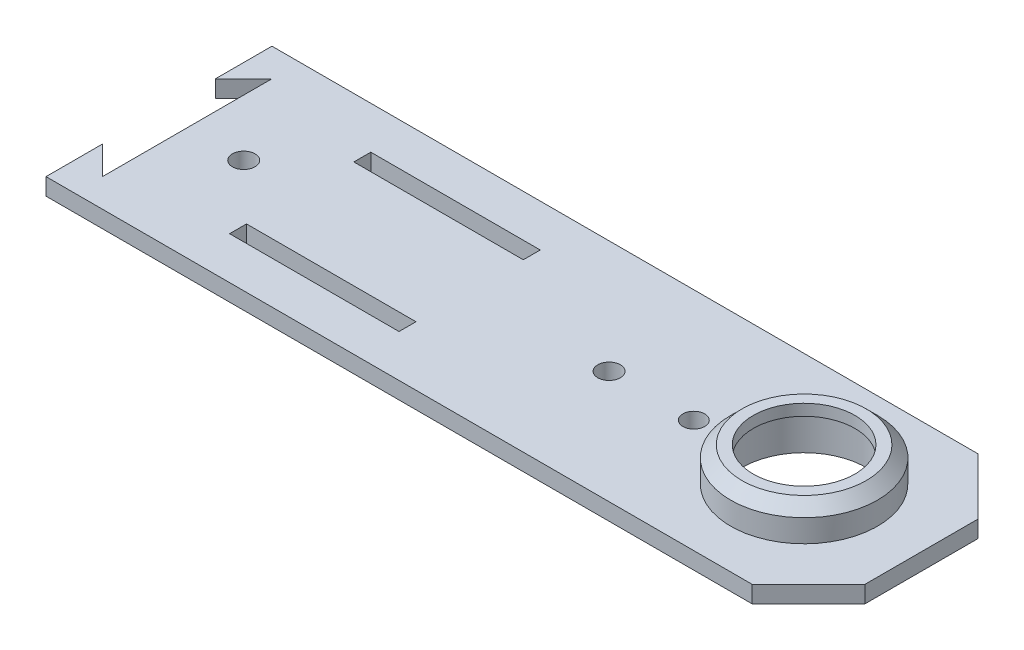
SolidWorks part; units mm, degrees
ref_plane "Alzado" through (0, 0, 0) normal (0, 0, 1) x (1, 0, 0)
ref_plane "Planta" through (0, 0, 0) normal (0, 1, 0) x (1, 0, 0)
ref_plane "Vista lateral" through (0, 0, 0) normal (1, 0, 0) x (0, 0, -1)
sketch "Croquis1" plane through (0, 0, 0) normal (0, 1, 0) x (1, 0, 0)
  line L0 (-67.5, 10) -> (-62.5, 15)
  line L1 (-67.5, -20) -> (67.5, -20)
  line L2 (-67.5, -20) -> (-67.5, -10)
  line L3 (-67.5, 20) -> (67.5, 20)
  line L4 (67.5, -20) -> (67.5, 20)
  line L5 (-67.5, -20) -> (67.5, 20) construction
  line L6 (-67.5, 20) -> (67.5, -20) construction
  line L7 (-62.5, 15) -> (-62.5, -15)
  line L8 (-62.5, -15) -> (-67.5, -10)
  line L9 (-67.5, 10) -> (-67.5, 20)
  line L11 (-42.5, 9.5) -> (-12.5, 9.5)
  line L12 (-42.5, 9.5) -> (-42.5, 12.5)
  line L13 (-42.5, 12.5) -> (-12.5, 12.5)
  line L14 (-12.5, 9.5) -> (-12.5, 12.5)
  line L15 (-42.5, 9.5) -> (-12.5, 12.5) construction
  line L16 (-42.5, 12.5) -> (-12.5, 9.5) construction
  line L17 (-42.5, -12.5) -> (-12.5, -12.5)
  line L18 (-42.5, -12.5) -> (-42.5, -9.5)
  line L19 (-42.5, -9.5) -> (-12.5, -9.5)
  line L20 (-12.5, -12.5) -> (-12.5, -9.5)
  line L21 (-42.5, -12.5) -> (-12.5, -9.5) construction
  line L22 (-42.5, -9.5) -> (-12.5, -12.5) construction
  circle A2 centre (46.714, 0) radius 11
  circle A3 centre (-52.5, 0) radius 2
  circle A4 centre (27.1858, 0) radius 1.9377
  circle A5 centre (12.1858, 0) radius 2
  point P0 (0, 0)
  point P8 (-62.5, 0)
  point P20 (-27.5, 11)
  point P28 (-27.5, -11)
  dimension "D6" = 15
  dimension "D7" = 22
  dimension "D11" = 10
  dimension "D12" = 4
  dimension "D1" = 40
  dimension "D2" = 135
  dimension "D3" = 45
  dimension "D4" = 20
  dimension "D5" = 30
  dimension "D8" = 30
  dimension "D9" = 3
  dimension "D10" = 40
  dimension "D13" = 12.5
  dimension "D14" = 12.5
extrude "Saliente-Extruir1" add sketch "Croquis1" along normal blind 3
sketch "Croquis2" plane through (0, 3, 0) normal (0, 1, 0) x (1, 0, 0)
  circle A0 centre (46.714, 0) radius 11
  circle A1 centre (46.714, 0) radius 13
  dimension "D1" = 2
extrude "Saliente-Extruir2" add sketch "Croquis2" along normal blind 4
sketch "Croquis3" plane through (0, 7, 0) normal (0, 1, 0) x (1, 0, 0)
  circle A0 centre (46.714, 0) radius 13
  circle A1 centre (46.714, 0) radius 9
  dimension "D1" = 18
extrude "Saliente-Extruir3" add sketch "Croquis3" along normal blind 2
chamfer "Chaflán1" distance 2 angle 45 1 edges at (46.714, 9, 13)
chamfer "Chaflán2" distance 10 angle 45 2 edges at (67.5, 1.5, -20) (67.5, 1.5, 20)
